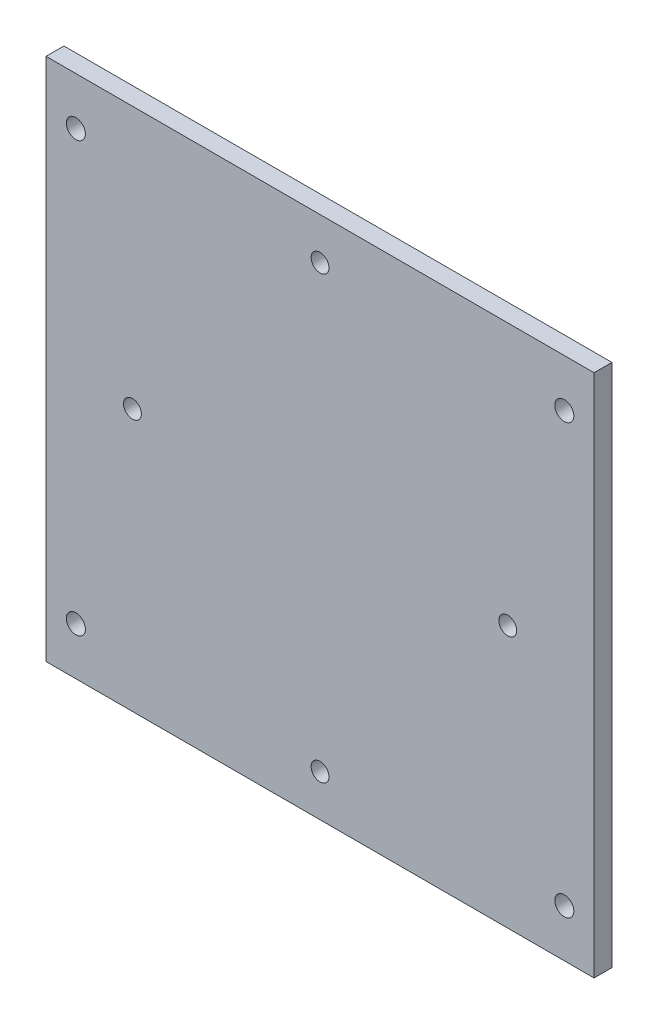
SolidWorks part; units mm, degrees
material "Thornel Mat VMA"
ref_plane "前视基准面" through (0, 0, 0) normal (0, 0, 1) x (1, 0, 0)
ref_plane "上视基准面" through (0, 0, 0) normal (0, 1, 0) x (1, 0, 0)
ref_plane "右视基准面" through (0, 0, 0) normal (1, 0, 0) x (0, 0, -1)
other "Configuration Table"
sketch "草图1" plane through (0, 0, 0) normal (0, 0, 1) x (1, 0, 0)
  line L0 (46, 0) -> (46, 10.5774) construction
  line L1 (0, 0) -> (92, 0)
  line L2 (0, 0) -> (0, 88)
  line L3 (0, 88) -> (92, 88)
  line L4 (92, 0) -> (92, 88)
  line L5 (0, 44) -> (9.7874, 44) construction
  line L7 (14.5, 81) -> (77.5, 81) construction
  line L8 (14.5, 81) -> (14.5, 7) construction
  line L9 (14.5, 7) -> (77.5, 7) construction
  line L10 (77.5, 81) -> (77.5, 7) construction
  circle A0 centre (5, 8) radius 1.6
  circle A1 centre (5, 80) radius 1.6
  circle A2 centre (87, 8) radius 1.6
  circle A3 centre (87, 80) radius 1.6
  circle A8 centre (46, 81) radius 1.5
  circle A9 centre (77.5, 44) radius 1.5
  circle A10 centre (46, 7) radius 1.5
  circle A11 centre (14.5, 44) radius 1.5
  dimension "D5" = 3.2
  dimension "D9" = 3
  dimension "D10" = 3
  dimension "D1" = 88
  dimension "D2" = 92
  dimension "D3" = 82
  dimension "D4" = 72
  dimension "D6" = 63
  dimension "D7" = 74
extrude "凸台-拉伸1" add sketch "草图1" along normal blind 3
